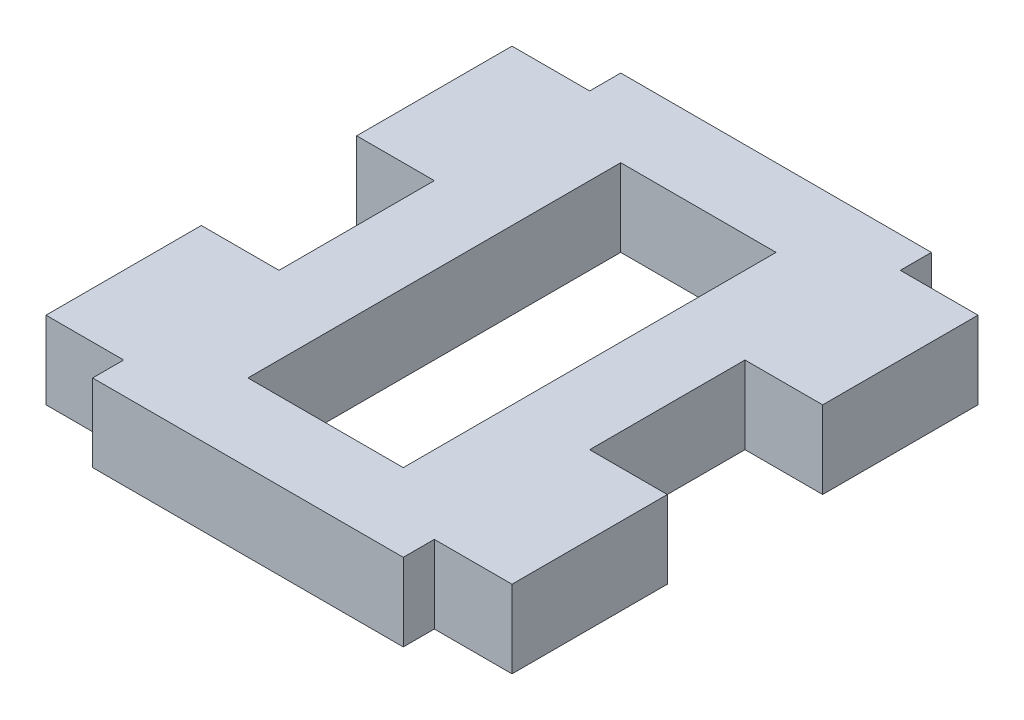
SolidWorks part; units mm, degrees
ref_plane "Front Plane" through (0, 0, 0) normal (0, 0, 1) x (1, 0, 0)
ref_plane "Top Plane" through (0, 0, 0) normal (0, 1, 0) x (1, 0, 0)
ref_plane "Right Plane" through (0, 0, 0) normal (1, 0, 0) x (0, 0, -1)
sketch "Sketch1" plane through (0, 0, 0) normal (0, 1, 0) x (1, 0, 0)
  line L1 (-12.7, -21.59) -> (12.7, -21.59)
  line L2 (-12.7, -21.59) -> (-12.7, 21.59)
  line L3 (-12.7, 21.59) -> (12.7, 21.59)
  line L4 (12.7, -21.59) -> (12.7, 21.59)
  line L5 (-12.7, -21.59) -> (12.7, 21.59) construction
  line L6 (-12.7, 21.59) -> (12.7, -21.59) construction
  point P0 (0, 0)
  dimension "D1" = 25.4
  dimension "D2" = 43.18
extrude "Boss-Extrude1" add sketch "Sketch1" along normal blind 6.35
sketch "Sketch2" plane through (0, 0, 0) normal (0, -1, 0) x (1, 0, 0)
  line L0 (-12.7, 19.05) -> (-19.05, 19.05)
  line L1 (-12.7, -21.59) -> (-12.7, 21.59) construction
  line L2 (-19.05, 19.05) -> (-19.05, 6.35)
  line L3 (-19.05, 6.35) -> (-12.7, 6.35)
  line L4 (-12.7, 6.35) -> (-12.7, 19.05)
  line L5 (-12.7, 0) -> (12.7, 0) construction
  line L6 (12.7, 21.59) -> (12.7, -21.59) construction
  line L7 (0, -21.59) -> (0, 21.59) construction
  line L8 (-12.7, 21.59) -> (12.7, 21.59) construction
  line L9 (12.7, 6.35) -> (12.7, 19.05)
  line L10 (19.05, 6.35) -> (12.7, 6.35)
  line L11 (19.05, 19.05) -> (19.05, 6.35)
  line L12 (12.7, 19.05) -> (19.05, 19.05)
  line L13 (12.7, -19.05) -> (19.05, -19.05)
  line L14 (19.05, -19.05) -> (19.05, -6.35)
  line L15 (19.05, -6.35) -> (12.7, -6.35)
  line L16 (12.7, -6.35) -> (12.7, -19.05)
  line L17 (-12.7, -6.35) -> (-12.7, -19.05)
  line L18 (-19.05, -6.35) -> (-12.7, -6.35)
  line L19 (-19.05, -19.05) -> (-19.05, -6.35)
  line L20 (-12.7, -19.05) -> (-19.05, -19.05)
  point P12 (0, 0)
  point P18 (0, 0)
  dimension "D1" = 12.7
  dimension "D2" = 6.35
  dimension "D3" = 6.35
extrude "Boss-Extrude2" add sketch "Sketch2" against normal up to surface (6.35 mm away) up to face at (0, 6.35, 0)
sketch "Sketch3" plane through (0, 0, 0) normal (0, -1, 0) x (1, 0, 0)
  line L0 (-12.7, 21.59) -> (12.7, 21.59) construction
  line L1 (-6.35, -15.24) -> (6.35, -15.24)
  line L2 (-6.35, -15.24) -> (-6.35, 15.24)
  line L3 (-6.35, 15.24) -> (6.35, 15.24)
  line L4 (6.35, -15.24) -> (6.35, 15.24)
  line L5 (-6.35, -15.24) -> (6.35, 15.24) construction
  line L6 (-6.35, 15.24) -> (6.35, -15.24) construction
  line L7 (12.7, 6.35) -> (12.7, -6.35) construction
  point P0 (0, 0)
  dimension "D1" = 6.35
  dimension "D2" = 6.35
extrude "Cut-Extrude1" cut sketch "Sketch3" against normal through all
